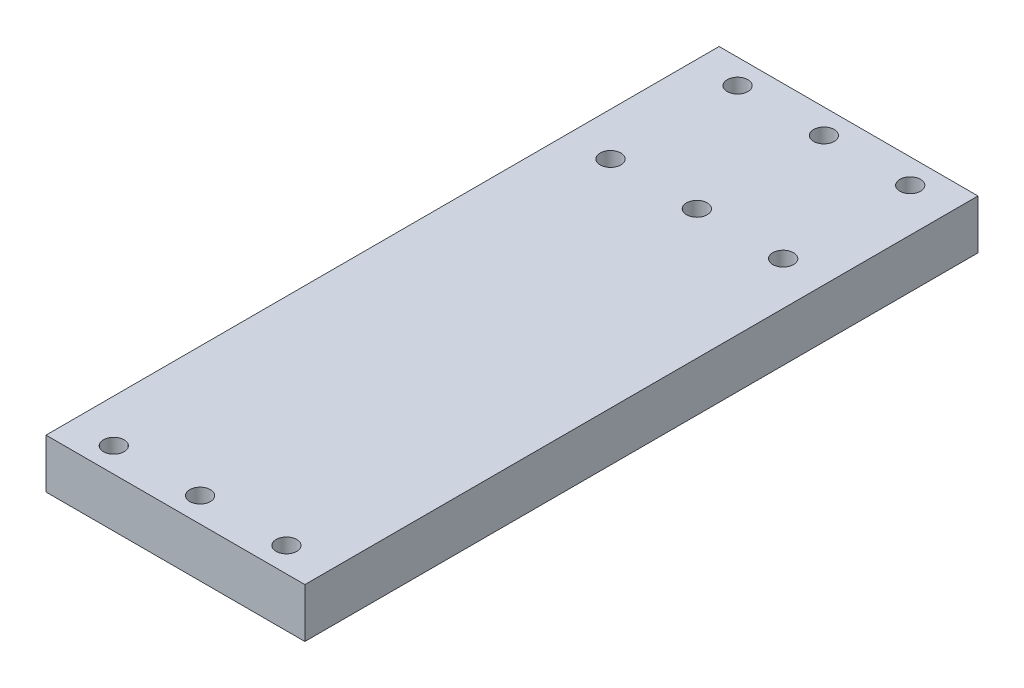
SolidWorks part; units mm, degrees
ref_plane "Front Plane" through (0, 0, 0) normal (0, 0, 1) x (1, 0, 0)
ref_plane "Top Plane" through (0, 0, 0) normal (0, 1, 0) x (1, 0, 0)
ref_plane "Right Plane" through (0, 0, 0) normal (1, 0, 0) x (0, 0, -1)
sketch "Sketch1" plane through (0, 0, 0) normal (0, 1, 0) x (1, 0, 0)
  line L1 (-25, -65) -> (25, -65)
  line L2 (-25, -65) -> (-25, 65)
  line L3 (-25, 65) -> (25, 65)
  line L4 (25, -65) -> (25, 65)
  line L5 (-25, -65) -> (25, 65) construction
  line L6 (-25, 65) -> (25, -65) construction
  point P0 (0, 0)
  dimension "D1" = 50
  dimension "D2" = 130
extrude "Boss-Extrude1" add sketch "Sketch1" along normal blind 9.525
sketch "Sketch3" plane through (0, 0, 0) normal (0, -1, 0) x (1, 0, 0)
  circle A0 centre (-16.67, -35.7) radius 1.65 construction
  circle A1 centre (0, -35.7) radius 1.65 construction
  circle A2 centre (16.67, -35.7) radius 1.65 construction
  circle A3 centre (-16.67, -35.7) radius 1.65 construction
  circle A4 centre (0, -35.7) radius 1.65 construction
  circle A5 centre (16.67, -35.7) radius 1.65 construction
  circle A6 centre (-16.67, 60.2375) radius 1.65 construction
  circle A7 centre (0, 60.2375) radius 1.65 construction
  circle A8 centre (16.67, 60.2375) radius 1.65 construction
  circle A9 centre (-16.67, -60.2375) radius 1.65 construction
  circle A10 centre (0, -60.2375) radius 1.65 construction
  circle A11 centre (16.67, -60.2375) radius 1.65 construction
  circle A12 centre (-16.67, 60.2375) radius 1.65 construction
  circle A13 centre (0, 60.2375) radius 1.65 construction
  circle A14 centre (16.67, 60.2375) radius 1.65 construction
  circle A15 centre (-16.67, -60.2375) radius 1.65 construction
  circle A16 centre (0, -60.2375) radius 1.65 construction
  circle A17 centre (16.67, -60.2375) radius 1.65 construction
  point P28 (-16.67, -35.7)
  point P31 (0, -35.7)
  point P34 (16.67, -35.7)
  point P57 (16.67, 60.2375)
  point P60 (0, 60.2375)
  point P63 (-16.67, 60.2375)
  point P66 (16.67, -60.2375)
  point P69 (0, -60.2375)
  point P72 (-16.67, -60.2375)
hole_wizard "Ø4.0mm Dowel Hole1" positions "Sketch3" profile "Sketch4" hole size "Ø4.0" standard "ANSI Metric" end condition through all
sketch "Sketch4" plane through (-16.67, 0, -60.2375) normal (1, 0, 0) x (0, 0, -1)
  line L0 (0, 0) -> (0, 9.525)
  line L1 (0, 9.525) -> (2, 9.525)
  line L2 (2, 9.525) -> (2, 0)
  line L5 (2, 0) -> (0, 0)
  line L11 (0, -6.35) -> (0, 107.95) construction
  dimension "Thru Hole Dia." = 4
  dimension "Thru Hole Depth" = 9.525
